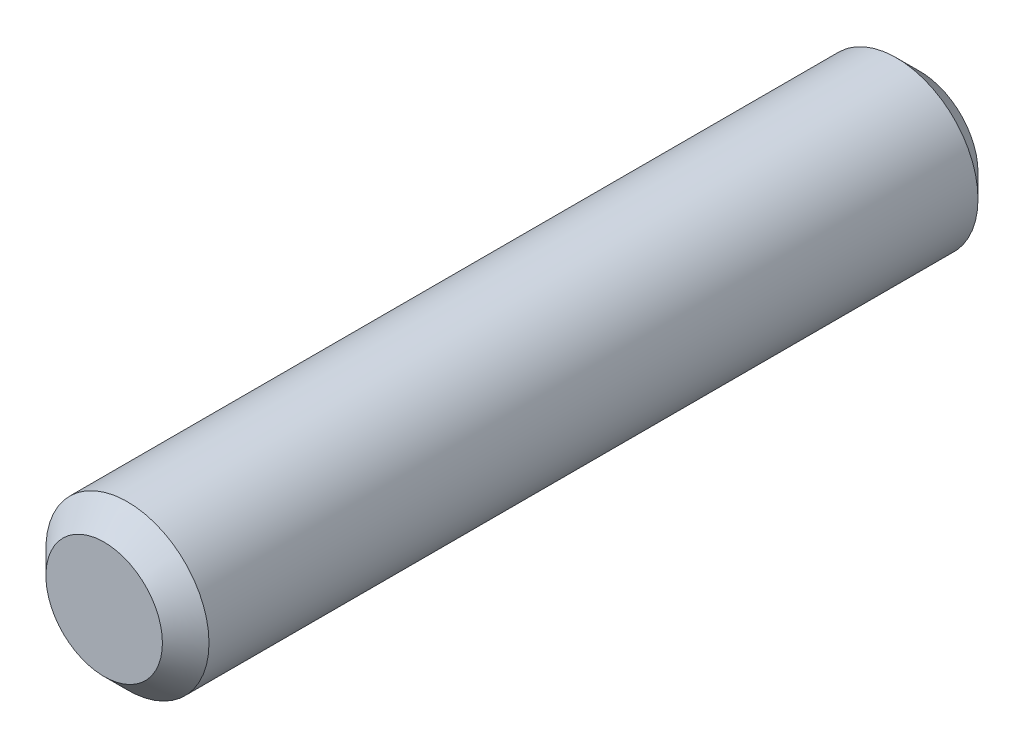
SolidWorks part; units mm, degrees
ref_plane "Front Plane" through (0, 0, 0) normal (0, 0, 1) x (1, 0, 0)
ref_plane "Top Plane" through (0, 0, 0) normal (0, 1, 0) x (1, 0, 0)
ref_plane "Right Plane" through (0, 0, 0) normal (1, 0, 0) x (0, 0, -1)
sketch "Sketch2" plane through (0, 0, 0) normal (0, 0, 1) x (1, 0, 0)
  circle A0 centre (0, 0) radius 7
  dimension "D1" = 14
extrude "Boss-Extrude1" add sketch "Sketch2" along normal mid plane 70
chamfer "Chamfer1" distance 2 angle 45 2 edges at (7, 0, 35) (7, 0, -35)
